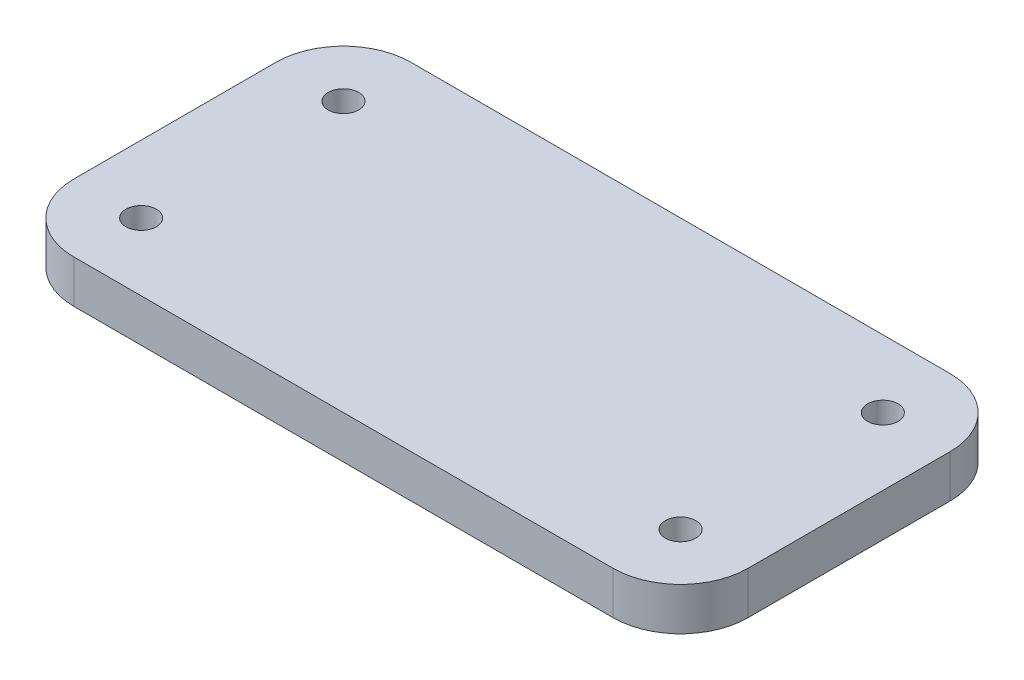
SolidWorks part; units mm, degrees
ref_plane "Front Plane" through (0, 0, 0) normal (0, 0, 1) x (1, 0, 0)
ref_plane "Top Plane" through (0, 0, 0) normal (0, 1, 0) x (1, 0, 0)
ref_plane "Right Plane" through (0, 0, 0) normal (1, 0, 0) x (0, 0, -1)
sketch "Sketch1" plane through (0, 0, 0) normal (0, 1, 0) x (1, 0, 0)
  line L1 (0, 0) -> (50, 0)
  line L2 (0, 0) -> (0, -25)
  line L3 (0, -25) -> (50, -25)
  line L4 (50, 0) -> (50, -25)
  line L5 (5, -5) -> (45, -5) construction
  line L6 (5, -5) -> (5, -20) construction
  line L7 (5, -20) -> (45, -20) construction
  line L8 (45, -5) -> (45, -20) construction
  circle A0 centre (5, -5) radius 1.13
  circle A1 centre (45, -5) radius 1.13
  circle A2 centre (45, -20) radius 1.13
  circle A3 centre (5, -20) radius 1.13
  point P13 (25, -5)
  point P14 (25, 0)
  dimension "D3" = 2.26
  dimension "D1" = 50
  dimension "D2" = 25
  dimension "D4" = 40
  dimension "D5" = 15
  dimension "D6" = 5
extrude "Boss-Extrude1" add sketch "Sketch1" along normal blind 3.175
fillet "Fillet1" radius 5 4 edges at (0, 1.5875, 0) (50, 1.5875, 0) (50, 1.5875, 25) (0, 1.5875, 25)
hole_wizard "#4-40 Tapped Hole1" positions "3DSketch1" profile "Sketch2" tap size "#4-40" standard "ANSI Inch" end condition through all
sketch3d "3DSketch1"
  line L0 (5, 3.175, 5) -> (5, 0, 5) construction
  line L1 (45, 3.175, 5) -> (45, 0, 5) construction
  line L2 (45, 3.175, 20) -> (45, 0, 20) construction
  line L3 (5, 3.175, 20) -> (5, 0, 20) construction
  point P0 (5, 3.175, 5)
  point P4 (45, 3.175, 5)
  point P8 (45, 3.175, 20)
  point P12 (5, 0, 20)
sketch "Sketch2" plane through (5, 3.175, 5) normal (1, 0, 0) x (0, 0, 1)
  line L0 (0, 0) -> (0, 3.175)
  line L1 (0, 3.175) -> (1.1303, 3.175)
  line L2 (1.1303, 3.175) -> (1.1303, 0)
  line L5 (1.1303, 0) -> (0, 0)
  line L11 (0, -6.35) -> (0, 107.95) construction
  dimension "Thru Tap Drill Dia." = 2.2606
  dimension "Thru Tap Drill Depth" = 3.175
cosmetic thread "Hole Thread1" parameters "D2"=2.8448
cosmetic thread "Hole Thread2" parameters "D2"=2.8448
cosmetic thread "Hole Thread3" parameters "D2"=2.8448
cosmetic thread "Hole Thread4" parameters "D2"=2.8448
